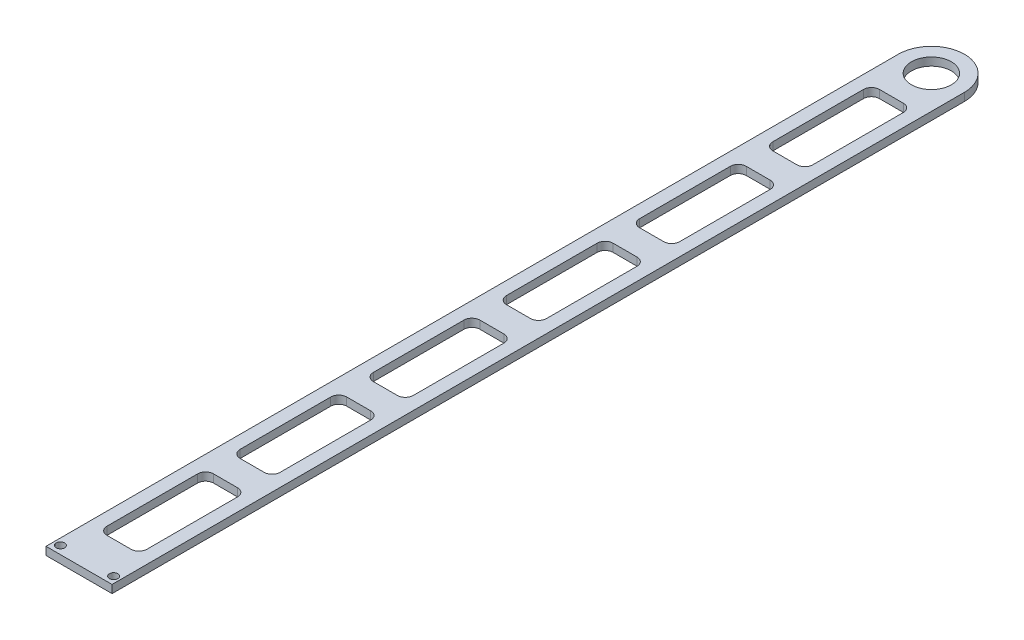
SolidWorks part; units mm, degrees
material "Hexcel AS4C (3000 丝)"
ref_plane "前视基准面" through (0, 0, 0) normal (0, 0, 1) x (1, 0, 0)
ref_plane "上视基准面" through (0, 0, 0) normal (0, 1, 0) x (1, 0, 0)
ref_plane "右视基准面" through (0, 0, 0) normal (1, 0, 0) x (0, 0, -1)
sketch "草图1" plane through (0, 0, 0) normal (0, 1, 0) x (1, 0, 0)
  line L0 (0, 0) -> (0, 320) construction
  line L1 (-12.4, 320) -> (-12.4, 0)
  line L2 (12.4, 320) -> (12.4, 0)
  line L3 (-12.4, 0) -> (12.4, 0)
  line L4 (-7.5, 255) -> (-7.5, 215)
  line L5 (-7.5, 305) -> (7.5, 305)
  line L6 (-7.5, 305) -> (-7.5, 265)
  line L7 (-7.5, 265) -> (7.5, 265)
  line L8 (7.5, 305) -> (7.5, 265)
  line L9 (-7.5, 305) -> (7.5, 265) construction
  line L10 (-7.5, 265) -> (7.5, 305) construction
  line L11 (-7.5, 255) -> (7.5, 255)
  line L12 (7.5, 255) -> (7.5, 215)
  line L13 (-7.5, 215) -> (7.5, 215)
  line L14 (-7.5, 205) -> (-7.5, 165)
  line L15 (-7.5, 205) -> (7.5, 205)
  line L16 (7.5, 205) -> (7.5, 165)
  line L17 (-7.5, 165) -> (7.5, 165)
  line L18 (-7.5, 155) -> (-7.5, 115)
  line L19 (-7.5, 155) -> (7.5, 155)
  line L20 (7.5, 155) -> (7.5, 115)
  line L21 (-7.5, 115) -> (7.5, 115)
  line L22 (-7.5, 105) -> (-7.5, 65)
  line L23 (-7.5, 105) -> (7.5, 105)
  line L24 (7.5, 105) -> (7.5, 65)
  line L25 (-7.5, 65) -> (7.5, 65)
  line L26 (-7.5, 55) -> (-7.5, 15)
  line L27 (-7.5, 55) -> (7.5, 55)
  line L28 (7.5, 55) -> (7.5, 15)
  line L29 (-7.5, 15) -> (7.5, 15)
  circle A0 centre (0, 320) radius 7.5
  arc A1 (12.4, 320) -> (-12.4, 320) centre (0, 320) ccw
  circle A2 centre (10, 3) radius 1.6
  circle A3 centre (-10, 3) radius 1.6
  point P4 (0, 285)
  dimension "D2" = 15
  dimension "D3" = 4.9
  dimension "D4" = 3
  dimension "D5" = 3.2
  dimension "D6" = 20
  dimension "D1" = 320
  dimension "D7" = 35
  dimension "D8" = 40
  dimension "D9" = 15
  dimension "D11" = 50
  dimension "D10" = 6
extrude "凸台-拉伸1" add sketch "草图1" along normal blind 3
fillet "圆角1" radius 3 24 edges at (7.5, 1.5, -55) (-7.5, 1.5, -55) (-7.5, 1.5, -15) (7.5, 1.5, -15) (7.5, 1.5, -105) (-7.5, 1.5, -105) (-7.5, 1.5, -65) (7.5, 1.5, -65) (7.5, 1.5, -155) (-7.5, 1.5, -155) (-7.5, 1.5, -115) (7.5, 1.5, -115) (7.5, 1.5, -205) (-7.5, 1.5, -205) (-7.5, 1.5, -165) (7.5, 1.5, -165) (7.5, 1.5, -255) (-7.5, 1.5, -255) (-7.5, 1.5, -215) (7.5, 1.5, -215) (-7.5, 1.5, -305) (-7.5, 1.5, -265) (7.5, 1.5, -265) (7.5, 1.5, -305)
